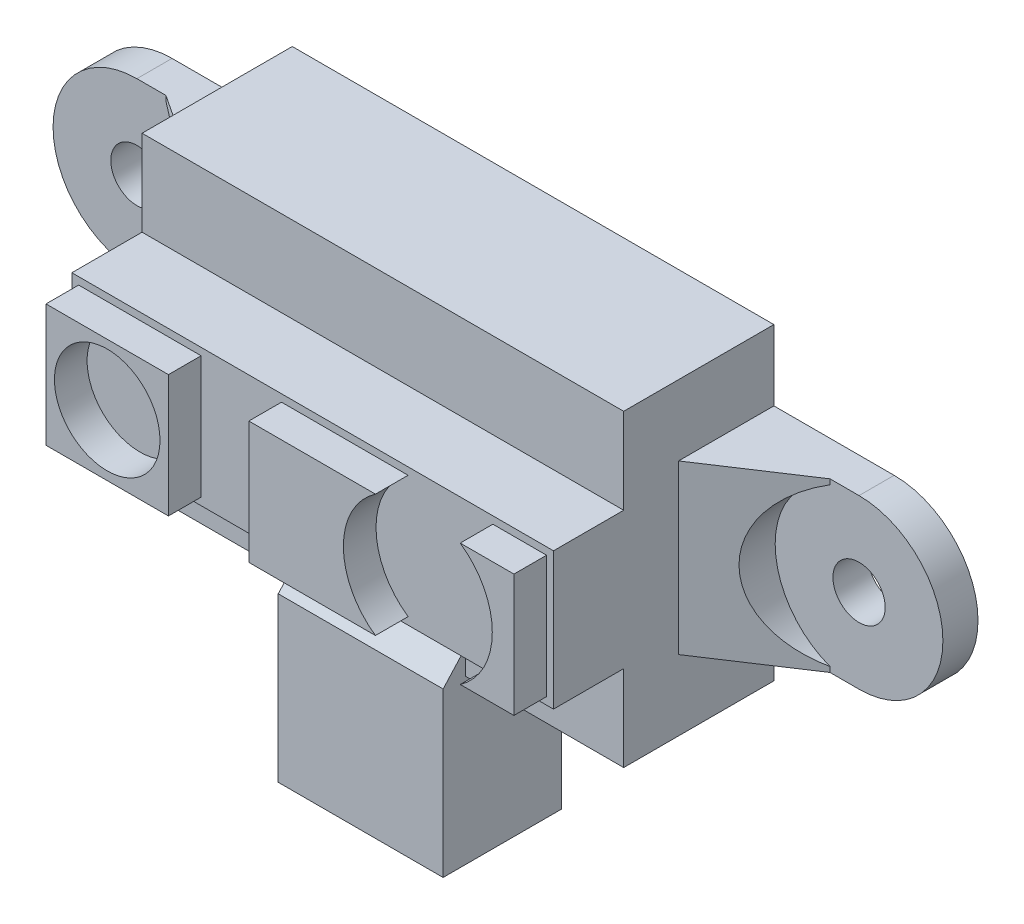
SolidWorks part; units mm, degrees
ref_plane "Front Plane" through (0, 0, 0) normal (0, 0, 1) x (1, 0, 0)
ref_plane "Top Plane" through (0, 0, 0) normal (0, 1, 0) x (1, 0, 0)
ref_plane "Right Plane" through (0, 0, 0) normal (1, 0, 0) x (0, 0, -1)
sketch "Sketch1" plane through (0, 0, 0) normal (0, 0, 1) x (1, 0, 0)
  line L1 (6.0261, 19.19) -> (35.5261, 19.19)
  line L2 (6.0261, 19.19) -> (6.0261, 14.8765)
  line L3 (6.0261, 0.29) -> (35.5261, 0.29)
  line L4 (35.5261, 19.19) -> (35.5261, 14.8765)
  line L5 (35.5261, 14.8765) -> (42.8914, 14.8765)
  line L6 (-1.3392, 4.6036) -> (6.0261, 4.6036)
  line L8 (-1.3392, 14.8765) -> (6.0261, 14.8765)
  line L13 (6.0261, 4.6036) -> (6.0261, 0.29)
  line L15 (35.5261, 4.6036) -> (42.8914, 4.6036)
  line L16 (35.5261, 4.6036) -> (35.5261, 0.29)
  arc A0 (-1.3392, 14.8765) -> (-1.3392, 4.6036) centre (-1.3392, 9.74) ccw
  arc A1 (42.8914, 14.8765) -> (42.8914, 4.6036) centre (42.8914, 9.74) cw
  circle A2 centre (-1.3392, 9.74) radius 1.6
  circle A3 centre (42.8914, 9.74) radius 1.6
  point P4 (20.7761, 9.74)
  point P5 (20.7761, 9.74)
  dimension "D4" = 3.2
  dimension "D1" = 44.2306
  dimension "D2" = 29.5
  dimension "D3" = 18.9
extrude "Boss-Extrude1" add sketch "Sketch1" along normal blind 13.5
sketch "Sketch2" plane through (0, 0, 0) normal (0, 1, 0) x (1, 0, 0)
  line L0 (-12.6003, -9.3) -> (57.125, -9.3) construction
  line L1 (6.0261, -13.5) -> (35.5261, -13.5) construction
  line L2 (-6.4757, -2.15) -> (-6.4757, 0)
  line L3 (-6.4757, 0) -> (-6.4757, -13.5) construction
  line L4 (-10.0449, 0) -> (-10.0449, -17.0497)
  line L5 (-10.0449, -17.0497) -> (6.0261, -17.0497)
  line L6 (6.0261, -13.5) -> (6.0261, 0) construction
  line L7 (6.0261, -17.0497) -> (6.0261, -5.8374)
  line L8 (6.0261, -5.8374) -> (0.4374, -2.15)
  line L9 (0.4374, -2.15) -> (-6.4757, -2.15)
  line L10 (-6.4757, 0) -> (-10.0449, 0)
  line L11 (20.7761, -15.8503) -> (20.7761, 2.246) construction
  line L12 (48.0278, 0) -> (51.597, 0)
  line L13 (41.1148, -2.15) -> (48.0278, -2.15)
  line L14 (35.5261, -5.8374) -> (41.1148, -2.15)
  line L15 (35.5261, -17.0497) -> (35.5261, -5.8374)
  line L16 (51.597, -17.0497) -> (35.5261, -17.0497)
  line L17 (51.597, 0) -> (51.597, -17.0497)
  line L18 (48.0278, -2.15) -> (48.0278, 0)
  dimension "D1" = 4.2
  dimension "D2" = 2.15
extrude "Cut-Extrude2" cut sketch "Sketch2" along normal through all
sketch "Sketch3" plane through (0, 0, 0) normal (1, 0, 0) x (0, 0, -1)
  line L0 (-13.5, 9.74) -> (0, 9.74) construction
  line L1 (-13.5, 19.19) -> (-9.2, 19.19)
  line L2 (-13.5, 19.19) -> (-13.5, 13.94)
  line L3 (-13.5, 13.94) -> (-9.2, 13.94)
  line L4 (-9.2, 19.19) -> (-9.2, 13.94)
  line L5 (-13.5, 19.19) -> (-13.5, 0.29) construction
  line L6 (0, 4.6036) -> (0, 14.8765) construction
  line L7 (-9.2, 0.29) -> (-9.2, 5.54)
  line L8 (-13.5, 5.54) -> (-9.2, 5.54)
  line L9 (-13.5, 0.29) -> (-13.5, 5.54)
  line L10 (-13.5, 0.29) -> (-9.2, 0.29)
  dimension "D1" = 4.3
  dimension "D2" = 8.4
extrude "Cut-Extrude4" cut sketch "Sketch3" along normal through all
sketch "Sketch4" plane through (0, 0, 13.5) normal (0, 0, 1) x (1, 0, 0)
  line L1 (6.4415, 13.4935) -> (13.9415, 13.4935)
  line L2 (6.4415, 13.4935) -> (6.4415, 5.9935)
  line L3 (6.4415, 5.9935) -> (13.9415, 5.9935)
  line L4 (13.9415, 13.4935) -> (13.9415, 5.9935)
  line L5 (35.1026, 13.4935) -> (31.8132, 13.4935)
  line L6 (35.1026, 13.4935) -> (35.1026, 5.9935)
  line L7 (35.1026, 5.9935) -> (31.8132, 5.9935)
  line L8 (18.8659, 13.4935) -> (18.8659, 5.9935)
  line L9 (26.6204, 13.4935) -> (18.8659, 13.4935)
  line L10 (26.6204, 5.9935) -> (18.8659, 5.9935)
  line L12 (6.0261, 13.94) -> (6.0261, 5.54)
  line L13 (6.0261, 5.54) -> (35.5261, 5.54)
  line L14 (35.5261, 5.54) -> (35.5261, 13.94)
  line L15 (35.5261, 13.94) -> (6.0261, 13.94)
  line L16 (6.0261, 13.94) -> (6.0261, 5.54) construction
  line L18 (35.5261, 5.54) -> (35.5261, 13.94) construction
  circle A0 centre (10.1915, 9.7435) radius 3.2334
  arc A1 (26.6204, 13.4935) -> (26.6204, 5.9935) centre (29.2168, 9.7435) ccw
  arc A2 (31.8132, 5.9935) -> (31.8132, 13.4935) centre (29.2168, 9.7435) ccw
  dimension "D2" = 7.5
  dimension "D1" = 0
extrude "Boss-Extrude2" add sketch "Sketch4" along normal blind 2
sketch "Sketch5" plane through (0, 0, 9.2) normal (0, 0, 1) x (1, 0, 0)
  circle A0 centre (-1.3392, 9.74) radius 5.1364
  circle A1 centre (42.8914, 9.74) radius 5.1364
extrude "Cut-Extrude6" cut sketch "Sketch5" against normal up to surface (7.05 mm away) up to face at (0.2608, 9.74, 2.15)
sketch "Sketch6" plane through (0, 0.29, 0) normal (0, -1, 0) x (1, 0, 0)
  line L0 (35.5261, 9.2) -> (35.5261, 0) construction
  line L1 (15.7261, 3.3) -> (25.8261, 3.3)
  line L2 (15.7261, 3.3) -> (15.7261, 10.5608)
  line L3 (15.7261, 10.5608) -> (25.8261, 10.5608)
  line L4 (25.8261, 3.3) -> (25.8261, 10.5608)
  line L5 (6.0261, 0) -> (35.5261, 0) construction
  point P4 (20.7761, 10.5608)
  dimension "D1" = 10.1
  dimension "D2" = 14.75
  dimension "D3" = 3.3
extrude "Boss-Extrude3" add sketch "Sketch6" along normal blind 10
sketch "Sketch7" plane through (25.8261, 0, 0) normal (1, 0, 0) x (0, 0, -1)
  line L0 (-10.5608, 0.29) -> (-9.2, 0.29)
  line L1 (-9.2, 0.29) -> (-9.2, 1.7877)
  line L2 (-9.2, 0.29) -> (-9.2, 5.54) construction
  line L3 (-9.2, 1.7877) -> (-10.5608, 0.29)
extrude "Boss-Extrude4" add sketch "Sketch7" against normal up to surface (10.1 mm away) up to face at (15.7261, -3.71, 7.3843)
